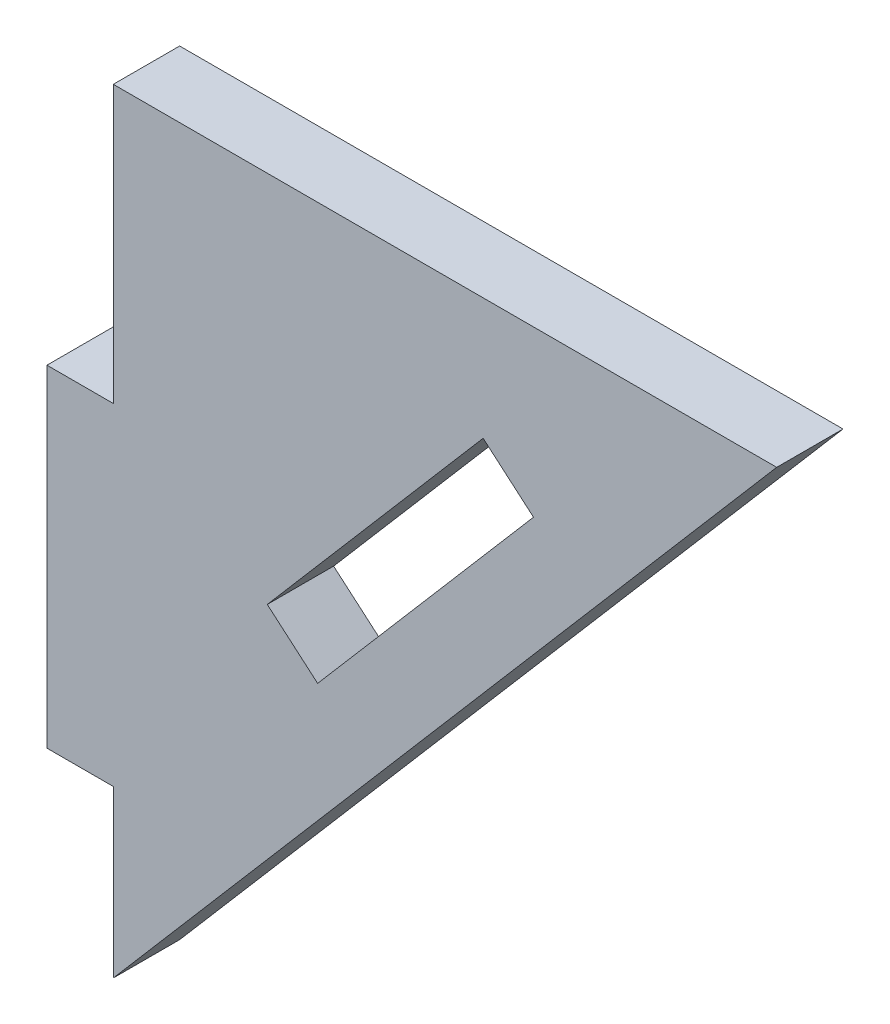
SolidWorks part; units mm, degrees
ref_plane "Front Plane" through (0, 0, 0) normal (0, 0, 1) x (1, 0, 0)
ref_plane "Top Plane" through (0, 0, 0) normal (0, 1, 0) x (1, 0, 0)
ref_plane "Right Plane" through (0, 0, 0) normal (1, 0, 0) x (0, 0, -1)
sketch "Sketch1" plane through (0, 0, 0) normal (0, 0, 1) x (1, 0, 0)
  line L0 (-15, -20) -> (15, 20)
  line L1 (15, -20) -> (-15, -20)
  line L2 (15, -20) -> (15, 20)
  line L3 (15, 20) -> (-15, 20)
  line L4 (-15, -20) -> (-15, 20)
  line L5 (15, -20) -> (-15, 20) construction
  line L6 (15, 20) -> (-15, -20) construction
  line L7 (-15, -15) -> (15, 20)
  line L8 (-18, 7.5) -> (-15, 7.5)
  line L9 (-18, 7.5) -> (-18, -7.5)
  line L10 (-18, -7.5) -> (-15, -7.5)
  line L11 (-15, 7.5) -> (-15, -7.5)
  line L12 (-18, 7.5) -> (-15, -7.5) construction
  line L13 (-18, -7.5) -> (-15, 7.5) construction
  line L14 (4.0025, 12.5476) -> (1.7247, 14.5)
  line L19 (4.0025, 12.5476) -> (-5.7594, 1.1588)
  line L20 (1.7247, 14.5) -> (-8.0372, 3.1112)
  line L21 (-5.7594, 1.1588) -> (-8.0372, 3.1112)
  point P0 (0, 0)
  point P6 (-16.5, 0)
  dimension "D1" = 40
  dimension "D2" = 3
  dimension "D3" = 15
  dimension "D4" = 30
  dimension "D5" = 5
  dimension "D6" = 3
  dimension "D7" = 15
  dimension "D8" = 3.5
  dimension "D9" = 5.5
extrude "Boss-Extrude1" add sketch "Sketch1" along normal blind 3 contours L4 L0 L3 | L9 L10 L4 L8
